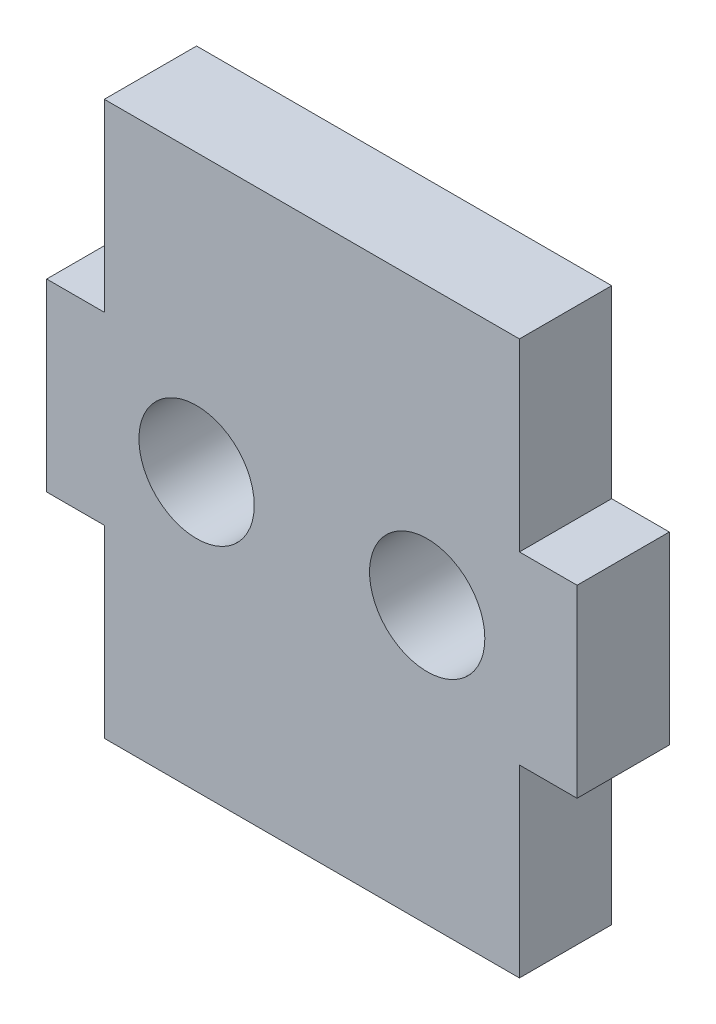
SolidWorks part; units mm, degrees
ref_plane "Front Plane" through (0, 0, 0) normal (0, 0, 1) x (1, 0, 0)
ref_plane "Top Plane" through (0, 0, 0) normal (0, 1, 0) x (1, 0, 0)
ref_plane "Right Plane" through (0, 0, 0) normal (1, 0, 0) x (0, 0, -1)
sketch "Model" plane through (0, 0, 0) normal (0, 0, 1) x (1, 0, 0)
  line L37 (1952.1768, 1458.8841) -> (1950.9268, 1458.8841)
  line L38 (1961.1768, 1458.8841) -> (1962.4268, 1458.8841)
  line L39 (1952.1768, 1454.8841) -> (1961.1768, 1454.8841)
  line L40 (1952.1768, 1458.8841) -> (1952.1768, 1454.8841)
  line L41 (1961.1768, 1458.8841) -> (1961.1768, 1454.8841)
  line L126 (1961.1768, 1462.8841) -> (1962.4268, 1462.8841)
  line L127 (1952.1768, 1462.8841) -> (1950.9268, 1462.8841)
  line L128 (1961.1768, 1466.8841) -> (1952.1768, 1466.8841)
  line L129 (1961.1768, 1462.8841) -> (1961.1768, 1466.8841)
  line L130 (1952.1768, 1462.8841) -> (1952.1768, 1466.8841)
  line L131 (1950.9268, 1462.8841) -> (1950.9268, 1458.8841)
  line L132 (1962.4268, 1462.8841) -> (1962.4268, 1458.8841)
  circle A81 centre (1959.1768, 1460.8841) radius 1.25
  circle A82 centre (1954.1768, 1460.8841) radius 1.25
  dimension "D1" = 2.5
  dimension "D2" = 1950.9268
  dimension "D3" = 1959.1768
  dimension "D4" = 1954.1768
  dimension "D5" = 1961.1768
  dimension "D6" = 1454.8841
  dimension "D7" = 1458.8841
  dimension "D8" = 1460.8841
extrude "Boss-Extrude1" add sketch "Model" along normal blind 2
